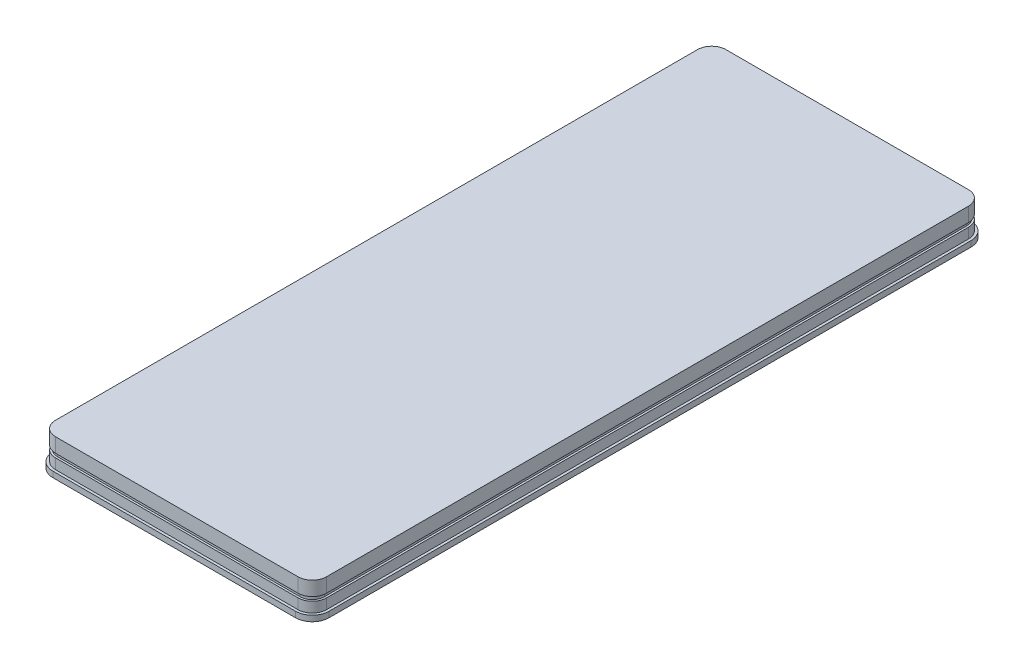
SolidWorks part; units mm, degrees
ref_plane "Front Plane" through (0, 0, 0) normal (0, 0, 1) x (1, 0, 0)
ref_plane "Top Plane" through (0, 0, 0) normal (0, 1, 0) x (1, 0, 0)
ref_plane "Right Plane" through (0, 0, 0) normal (1, 0, 0) x (0, 0, -1)
sketch "Sketch1" plane through (0, 0, 0) normal (0, 1, 0) x (1, 0, 0)
  line L1 (-42.5, -117.5) -> (42.5, -117.5)
  line L2 (-47.5, -112.5) -> (-47.5, 112.5)
  line L3 (-42.5, 117.5) -> (42.5, 117.5)
  line L4 (47.5, -112.5) -> (47.5, 112.5)
  line L5 (-47.5, -117.5) -> (47.5, 117.5) construction
  line L6 (-47.5, 117.5) -> (47.5, -117.5) construction
  arc A0 (-47.5, -112.5) -> (-42.5, -117.5) centre (-42.5, -112.5) ccw
  arc A1 (42.5, -117.5) -> (47.5, -112.5) centre (42.5, -112.5) ccw
  arc A2 (47.5, 112.5) -> (42.5, 117.5) centre (42.5, 112.5) ccw
  arc A3 (-47.5, 112.5) -> (-42.5, 117.5) centre (-42.5, 112.5) cw
  point P0 (0, 0)
  dimension "D3" = 5
  dimension "D1" = 95
  dimension "D2" = 235
extrude "Boss-Extrude1" add sketch "Sketch1" along normal blind 10
sketch "Sketch2" plane through (0, 0, 0) normal (0, -1, 0) x (1, 0, 0)
  line L8 (-48.4, 112.5) -> (-48.4, -112.5)
  line L9 (-42.5, -118.4) -> (42.5, -118.4)
  line L10 (48.4, -112.5) -> (48.4, 112.5)
  line L11 (42.5, 118.4) -> (-42.5, 118.4)
  line L12 (-48.4, 112.5) -> (-48.4, -112.5)
  line L13 (-42.5, -118.4) -> (42.5, -118.4)
  line L14 (48.4, -112.5) -> (48.4, 112.5)
  line L15 (42.5, 118.4) -> (-42.5, 118.4)
  arc A8 (-42.5, 118.4) -> (-48.4, 112.5) centre (-42.5, 112.5) ccw
  arc A9 (-48.4, -112.5) -> (-42.5, -118.4) centre (-42.5, -112.5) ccw
  arc A10 (42.5, -118.4) -> (48.4, -112.5) centre (42.5, -112.5) ccw
  arc A11 (48.4, 112.5) -> (42.5, 118.4) centre (42.5, 112.5) ccw
  arc A12 (-42.5, 118.4) -> (-48.4, 112.5) centre (-42.5, 112.5) ccw
  arc A13 (-48.4, -112.5) -> (-42.5, -118.4) centre (-42.5, -112.5) ccw
  arc A14 (42.5, -118.4) -> (48.4, -112.5) centre (42.5, -112.5) ccw
  arc A15 (48.4, 112.5) -> (42.5, 118.4) centre (42.5, 112.5) ccw
  dimension "D1" = 0.9
extrude "Boss-Extrude2" add sketch "Sketch2" along normal blind 2
sketch "Sketch3" plane through (0, 10, 0) normal (0, 1, 0) x (1, 0, 0)
  line L8 (-42.5, -116.8) -> (42.5, -116.8)
  line L9 (46.8, -112.5) -> (46.8, 112.5)
  line L10 (42.5, 116.8) -> (-42.5, 116.8)
  line L11 (-46.8, 112.5) -> (-46.8, -112.5)
  line L12 (-42.5, -116.8) -> (42.5, -116.8)
  line L13 (46.8, -112.5) -> (46.8, 112.5)
  line L14 (42.5, 116.8) -> (-42.5, 116.8)
  line L15 (-46.8, 112.5) -> (-46.8, -112.5)
  arc A8 (-46.8, -112.5) -> (-42.5, -116.8) centre (-42.5, -112.5) ccw
  arc A9 (42.5, -116.8) -> (46.8, -112.5) centre (42.5, -112.5) ccw
  arc A10 (46.8, 112.5) -> (42.5, 116.8) centre (42.5, 112.5) ccw
  arc A11 (-42.5, 116.8) -> (-46.8, 112.5) centre (-42.5, 112.5) ccw
  arc A12 (-46.8, -112.5) -> (-42.5, -116.8) centre (-42.5, -112.5) ccw
  arc A13 (42.5, -116.8) -> (46.8, -112.5) centre (42.5, -112.5) ccw
  arc A14 (46.8, 112.5) -> (42.5, 116.8) centre (42.5, 112.5) ccw
  arc A15 (-42.5, 116.8) -> (-46.8, 112.5) centre (-42.5, 112.5) ccw
  arc M9 (-47.5, -112.5) -> (-42.5, -117.5) centre (-42.5, -112.5) ccw
  line M10 (-42.5, -117.5) -> (42.5, -117.5)
  arc M11 (42.5, -117.5) -> (47.5, -112.5) centre (42.5, -112.5) ccw
  line M12 (47.5, -112.5) -> (47.5, 112.5)
  arc M13 (47.5, 112.5) -> (42.5, 117.5) centre (42.5, 112.5) ccw
  line M14 (42.5, 117.5) -> (-42.5, 117.5)
  arc M15 (-42.5, 117.5) -> (-47.5, 112.5) centre (-42.5, 112.5) ccw
  line M16 (-47.5, 112.5) -> (-47.5, -112.5)
  dimension "D1" = 0.7
extrude "Cut-Extrude1" cut sketch "Sketch3" against normal blind 1.4 from offset 5 contours A15 L14 A14 L13 A13 L12 A12 L15 M16 M9 M10 M11 M12 M13 M14 M15
